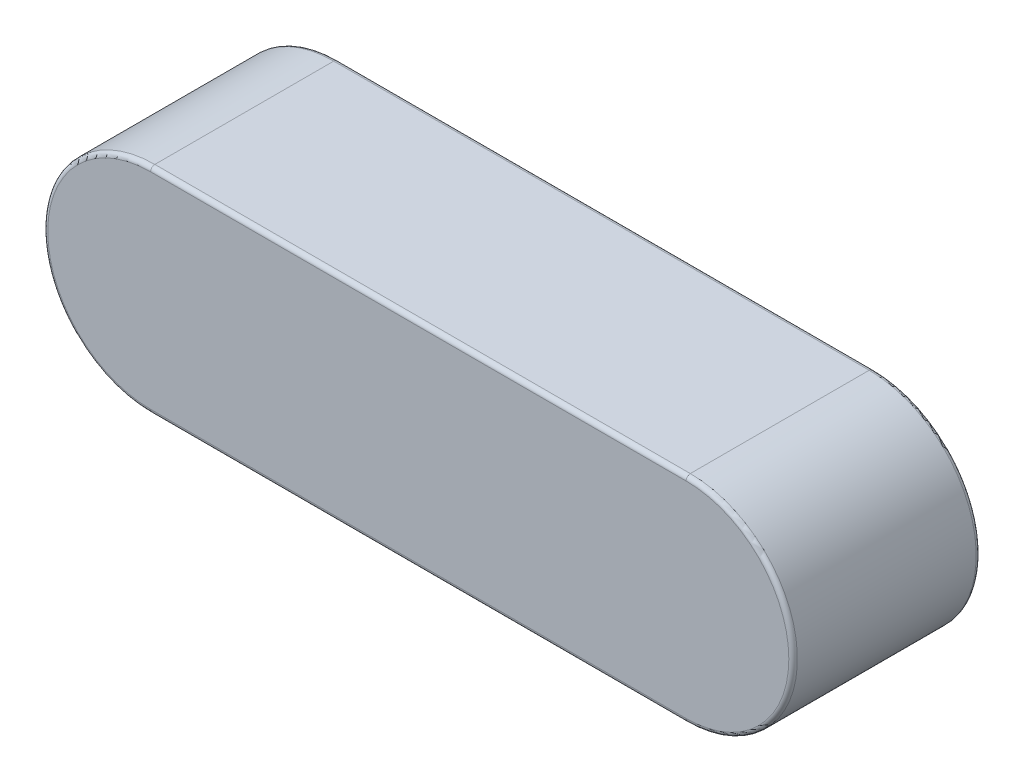
SolidWorks part; units mm, degrees
ref_plane "Спереди" through (0, 0, 0) normal (0, 0, 1) x (1, 0, 0)
ref_plane "Сверху" through (0, 0, 0) normal (0, 1, 0) x (1, 0, 0)
ref_plane "Справа" through (0, 0, 0) normal (1, 0, 0) x (0, 0, -1)
sketch "Эскиз1" plane through (0, 0, 0) normal (0, 0, 1) x (1, 0, 0)
  line L0 (0, 0) -> (20, 0) construction
  line L1 (0, 4) -> (20, 4)
  line L2 (0, -4) -> (20, -4)
  arc A0 (0, 4) -> (0, -4) centre (0, 0) ccw
  arc A1 (20, -4) -> (20, 4) centre (20, 0) ccw
  point P3 (10, 0)
  dimension "D1" = 20
  dimension "D2" = 8
extrude "Бобышка-Вытянуть1" add sketch "Эскиз1" along normal blind 7
fillet "Скругление1" radius 0.16 8 edges at (10, -4, 0) (24, 0, 0) (10, 4, 0) (-4, 0, 0) (10, 4, 7) (24, 0, 7) (10, -4, 7) (-4, 0, 7)
